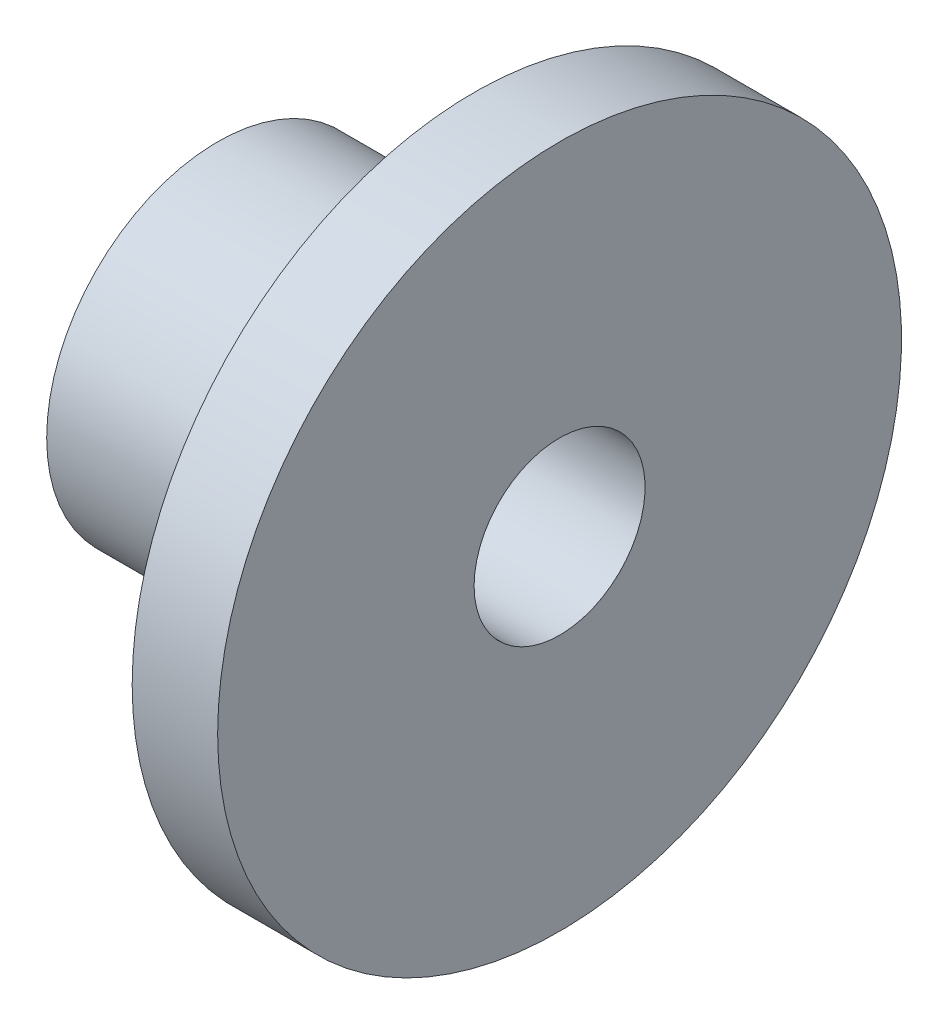
SolidWorks part; units mm, degrees
ref_plane "Front Plane" through (0, 0, 0) normal (0, 0, 1) x (1, 0, 0)
ref_plane "Top Plane" through (0, 0, 0) normal (0, 1, 0) x (1, 0, 0)
ref_plane "Right Plane" through (0, 0, 0) normal (1, 0, 0) x (0, 0, -1)
sketch "Sketch1" plane through (0, 0, 0) normal (0, 1, 0) x (1, 0, 0)
  line L0 (0, 2) -> (0, 4)
  line L1 (0, 4) -> (6, 4)
  line L2 (6, 4) -> (6, 8)
  line L3 (6, 8) -> (8, 8)
  line L4 (8, 8) -> (8, 2)
  line L5 (8, 2) -> (0, 2)
  line L6 (0, 0) -> (3.6529, 0) construction
  dimension "D1" = 2
  dimension "D2" = 4
  dimension "D3" = 8
  dimension "D4" = 2
  dimension "D5" = 8
revolve "Revolve1" add sketch "Sketch1" angle 360 about L6
